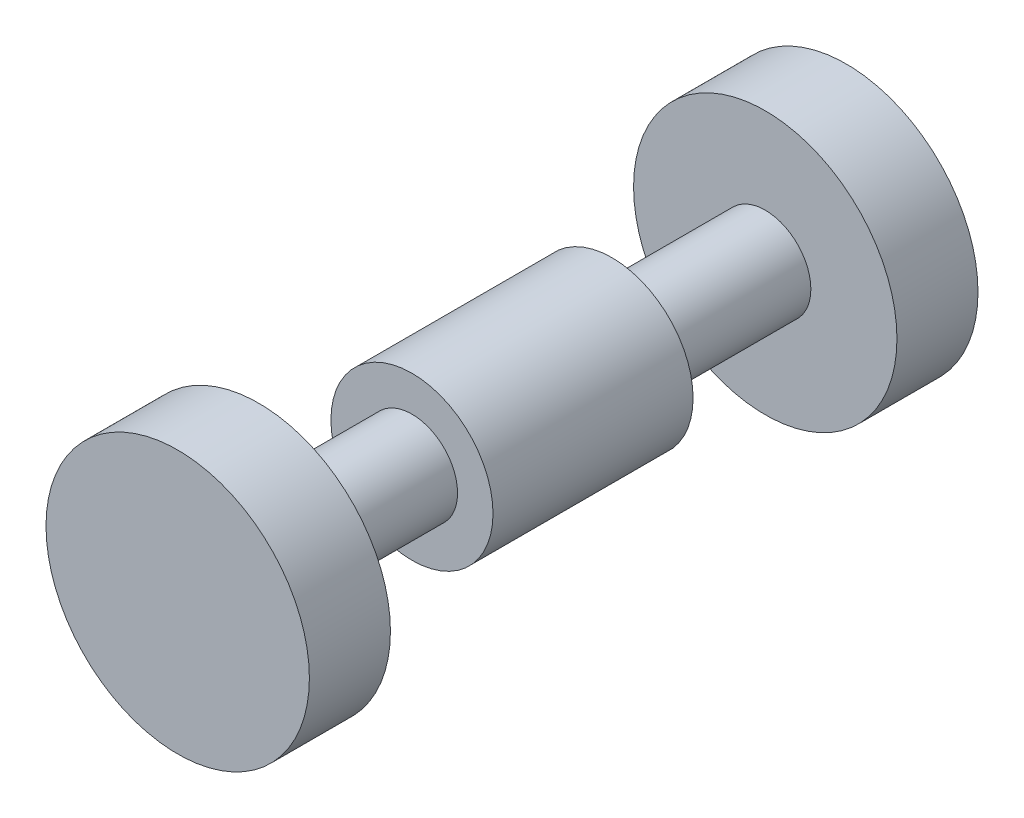
SolidWorks part; units mm, degrees
ref_plane "Front Plane" through (0, 0, 0) normal (0, 0, 1) x (1, 0, 0)
ref_plane "Top Plane" through (0, 0, 0) normal (0, 1, 0) x (1, 0, 0)
ref_plane "Right Plane" through (0, 0, 0) normal (1, 0, 0) x (0, 0, -1)
sketch "Sketch1" plane through (0, 0, 0) normal (0, 0, 1) x (1, 0, 0)
  circle A0 centre (0, 0) radius 0.9
  dimension "D1" = 1.8
extrude "Boss-Extrude1" add sketch "Sketch1" along normal mid plane 10
sketch "Sketch2" plane through (0, 0, 0) normal (0, 0, 1) x (1, 0, 0)
  circle A0 centre (0, 0) radius 1.6
  dimension "D1" = 3.2
extrude "Boss-Extrude2" add sketch "Sketch2" along normal mid plane 3.95
sketch "Sketch3" plane through (0, 0, 5) normal (0, 0, 1) x (1, 0, 0)
  circle A0 centre (0, 0) radius 2.6
  dimension "D1" = 5.2
extrude "Boss-Extrude3" add sketch "Sketch3" along normal blind 1.6
mirror "Mirror1" about plane through (0, 0, 0) normal (0, 0, 1) of "Boss-Extrude3"
